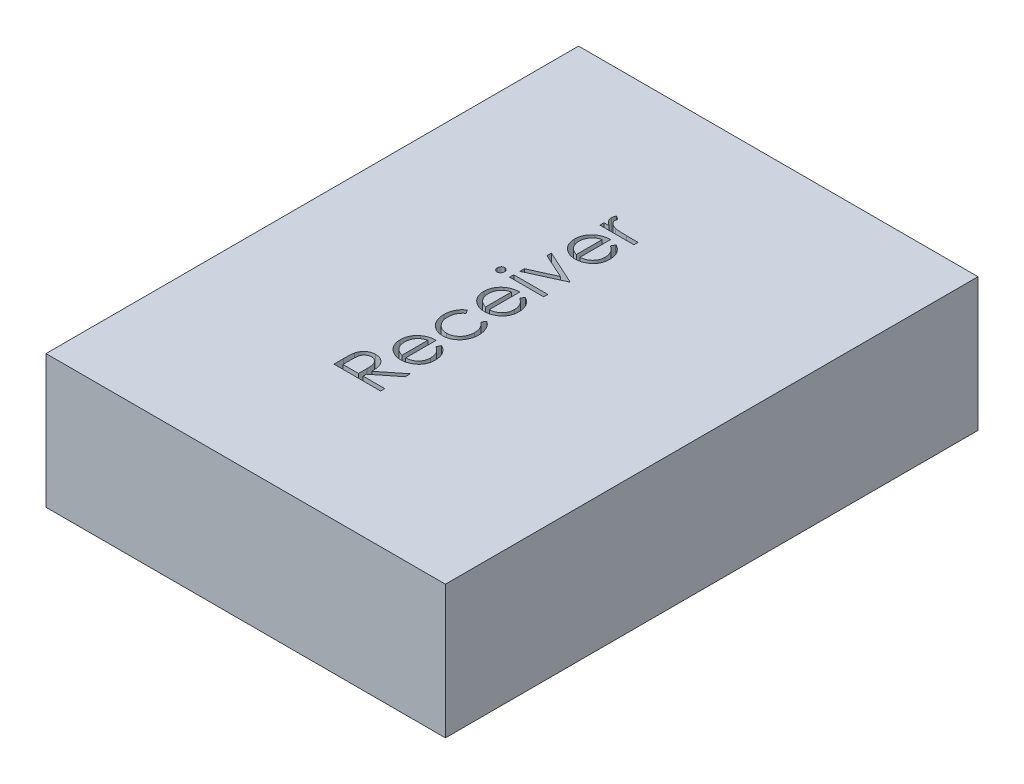
SolidWorks part; units mm, degrees
ref_plane "Front Plane" through (0, 0, 0) normal (0, 0, 1) x (1, 0, 0)
ref_plane "Top Plane" through (0, 0, 0) normal (0, 1, 0) x (1, 0, 0)
ref_plane "Right Plane" through (0, 0, 0) normal (1, 0, 0) x (0, 0, -1)
sketch "Sketch1" plane through (0, 0, 0) normal (0, 1, 0) x (1, 0, 0)
  line L1 (-15, 20) -> (15, 20)
  line L2 (-15, 20) -> (-15, -20)
  line L3 (-15, -20) -> (15, -20)
  line L4 (15, 20) -> (15, -20)
  line L5 (-15, 20) -> (15, -20) construction
  line L6 (-15, -20) -> (15, 20) construction
  point P0 (0, 0)
  dimension "D1" = 30
  dimension "D2" = 40
extrude "Boss-Extrude1" add sketch "Sketch1" along normal blind 10
sketch "Sketch2" plane through (0, 10, 0) normal (0, 1, 0) x (1, 0, 0)
  line L0 (0, -20) -> (0, 20) construction
  line L1 (-15, -20) -> (15, -20) construction
  line L2 (15, 20) -> (-15, 20) construction
  text T0 "Receiver"
extrude "Cut-Extrude1" cut sketch "Sketch2" against normal blind 2
